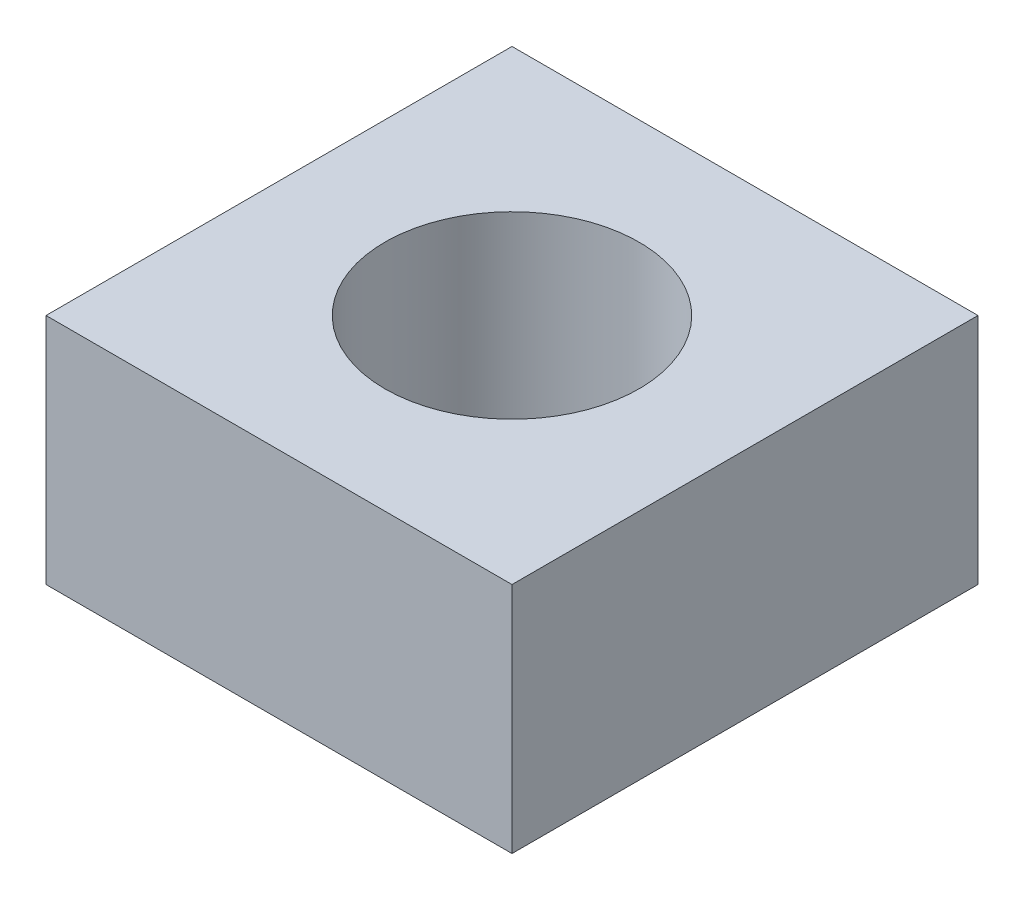
SolidWorks part; units mm, degrees
ref_plane "Front Plane" through (0, 0, 0) normal (0, 0, 1) x (1, 0, 0)
ref_plane "Top Plane" through (0, 0, 0) normal (0, 1, 0) x (1, 0, 0)
ref_plane "Right Plane" through (0, 0, 0) normal (1, 0, 0) x (0, 0, -1)
sketch "Sketch1" plane through (0, 0, 0) normal (0, 1, 0) x (1, 0, 0)
  line L1 (-5.5, -5.5) -> (5.5, -5.5)
  line L2 (-5.5, -5.5) -> (-5.5, 5.5)
  line L3 (-5.5, 5.5) -> (5.5, 5.5)
  line L4 (5.5, -5.5) -> (5.5, 5.5)
  line L5 (-5.5, -5.5) -> (5.5, 5.5) construction
  line L6 (-5.5, 5.5) -> (5.5, -5.5) construction
  circle A0 centre (0, 0) radius 3
  point P0 (0, 0)
  dimension "D2" = 6
  dimension "D1" = 11
extrude "Boss-Extrude1" add sketch "Sketch1" along normal blind 5.5
